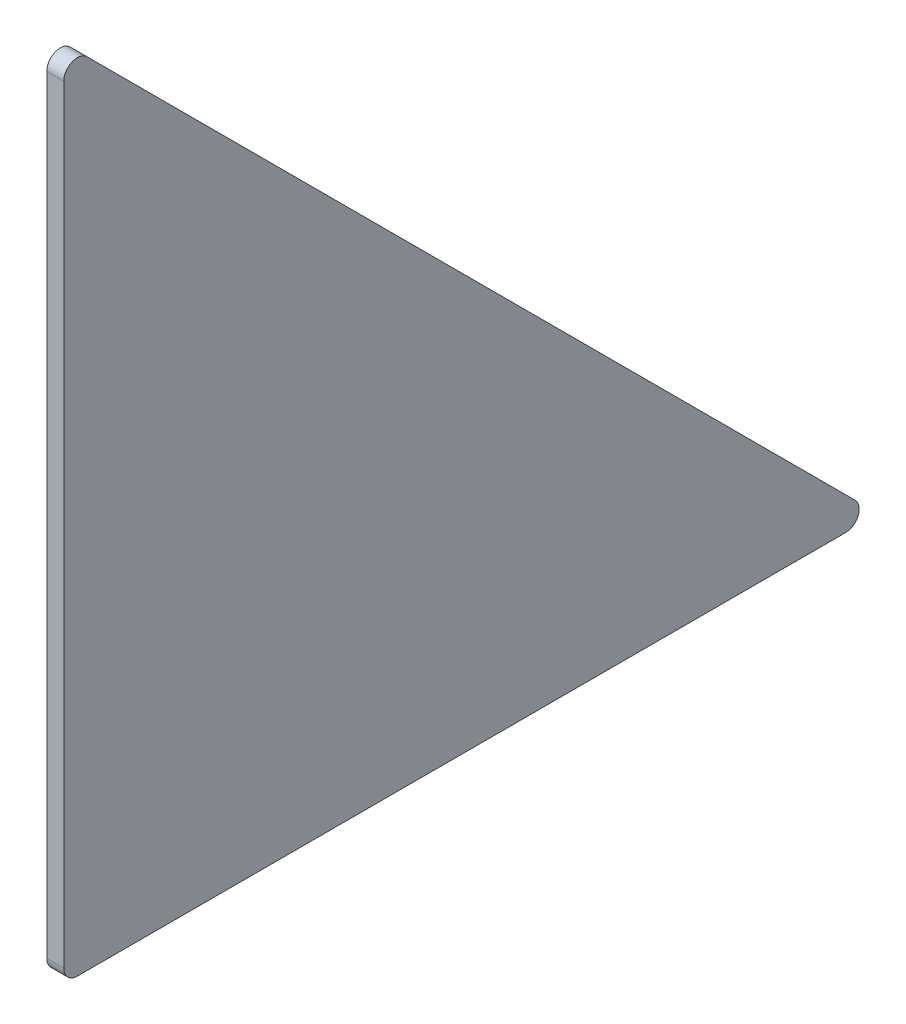
SolidWorks part; units mm, degrees
ref_plane "Front Plane" through (0, 0, 0) normal (0, 0, 1) x (1, 0, 0)
ref_plane "Top Plane" through (0, 0, 0) normal (0, 1, 0) x (1, 0, 0)
ref_plane "Right Plane" through (0, 0, 0) normal (1, 0, 0) x (0, 0, -1)
sketch "Sketch1" plane through (0, 0, 0) normal (1, 0, 0) x (0, 0, -1)
  line L0 (0, 0) -> (0, 152.4)
  line L1 (0, 152.4) -> (152.4, 0)
  line L2 (152.4, 0) -> (0, 0)
  dimension "D1" = 152.4
  dimension "D2" = 152.4
extrude "Boss-Extrude1" add sketch "Sketch1" along normal blind 3.175
fillet "Fillet1" radius 2.54 3 edges at (1.5875, 0, -152.4) (1.5875, 0, 0) (1.5875, 152.4, 0)
